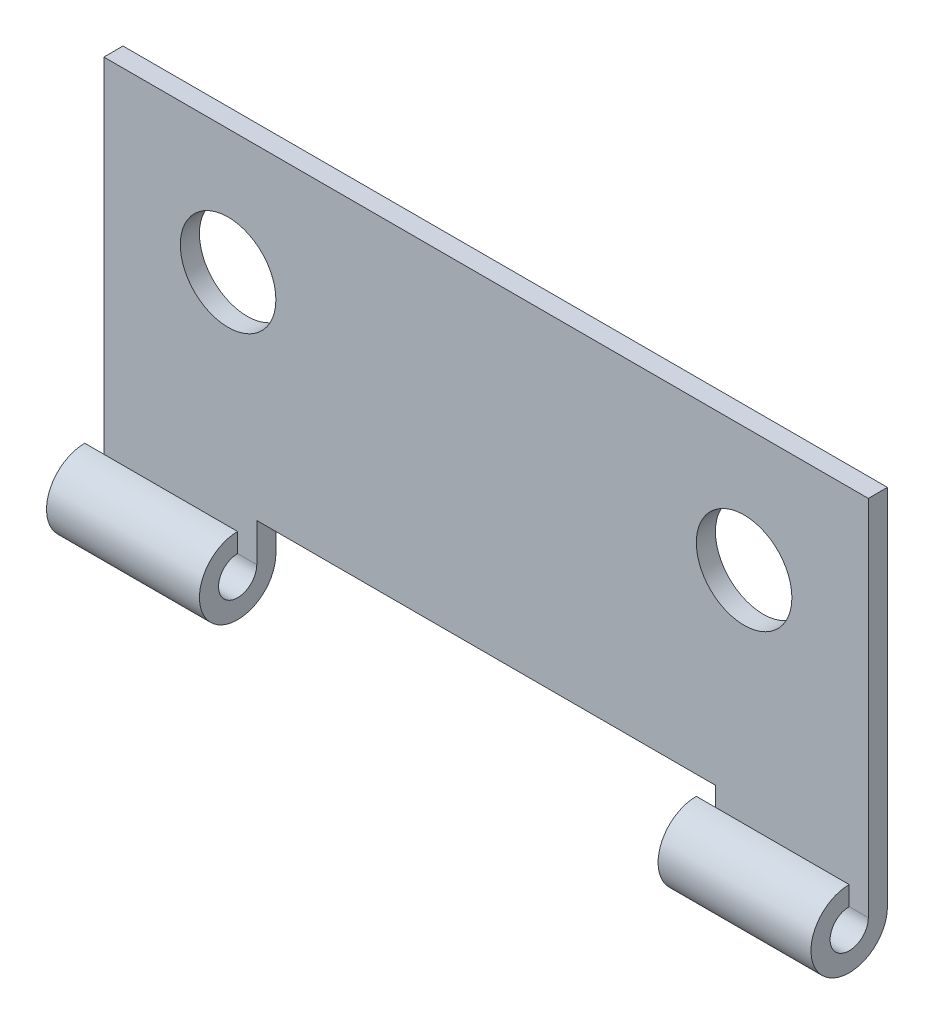
SolidWorks part; units mm, degrees
ref_plane "Plan de face" through (0, 0, 0) normal (0, 0, 1) x (1, 0, 0)
ref_plane "Plan de dessus" through (0, 0, 0) normal (0, 1, 0) x (1, 0, 0)
ref_plane "Plan de droite" through (0, 0, 0) normal (1, 0, 0) x (0, 0, -1)
sketch "Esquisse1" plane through (0, 0, 0) normal (0, 0, 1) x (1, 0, 0)
  line L1 (0, 0) -> (40, 0)
  line L2 (0, 0) -> (0, 17)
  line L3 (0, 17) -> (40, 17)
  line L4 (40, 0) -> (40, 17)
  dimension "D1" = 17
  dimension "D2" = 40
extrude "Boss.-Extru.1" add sketch "Esquisse1" along normal blind 1
sketch "Esquisse2" plane through (0, 0, 1) normal (0, 0, 1) x (1, 0, 0)
  line L0 (40, 17) -> (0, 17) construction
  line L1 (0, 17) -> (0, 0) construction
  line L2 (40, 0) -> (40, 17) construction
  circle A0 centre (6.5, 10.5) radius 2.5
  circle A1 centre (33.5, 10.5) radius 2.5
  dimension "D1" = 5
  dimension "D2" = 6.5
  dimension "D3" = 6.5
  dimension "D4" = 6.5
extrude "Enlèv. mat.-Extru.1" cut sketch "Esquisse2" against normal up to next
ref_plane "Plan1" through (8, 0, 0) normal (-1, 0, 0) x (0, 0, 1)
sketch "Esquisse3" plane through (8, 0, 0) normal (-1, 0, 0) x (0, 0, 1)
  line L0 (0, 0) -> (0, -2)
  line L1 (2, 0) -> (2, -1)
  line L2 (1, -2) -> (1, 0)
  line L3 (0, 0) -> (1, 0)
  arc A0 (0, -2) -> (2, 0) centre (2, -2) ccw
  arc A1 (2, -1) -> (1, -2) centre (2, -2) cw
  dimension "D1" = 2
  dimension "D2" = 1
  dimension "D3" = 1
extrude "Boss.-Extru.2" add sketch "Esquisse3" along normal blind 8
ref_plane "Plan2" through (20, 0, 0) normal (-1, 0, 0) x (0, 0, 1)
mirror "Symétrie1" about plane through (20, 0, 0) normal (-1, 0, 0) of "Boss.-Extru.2"
